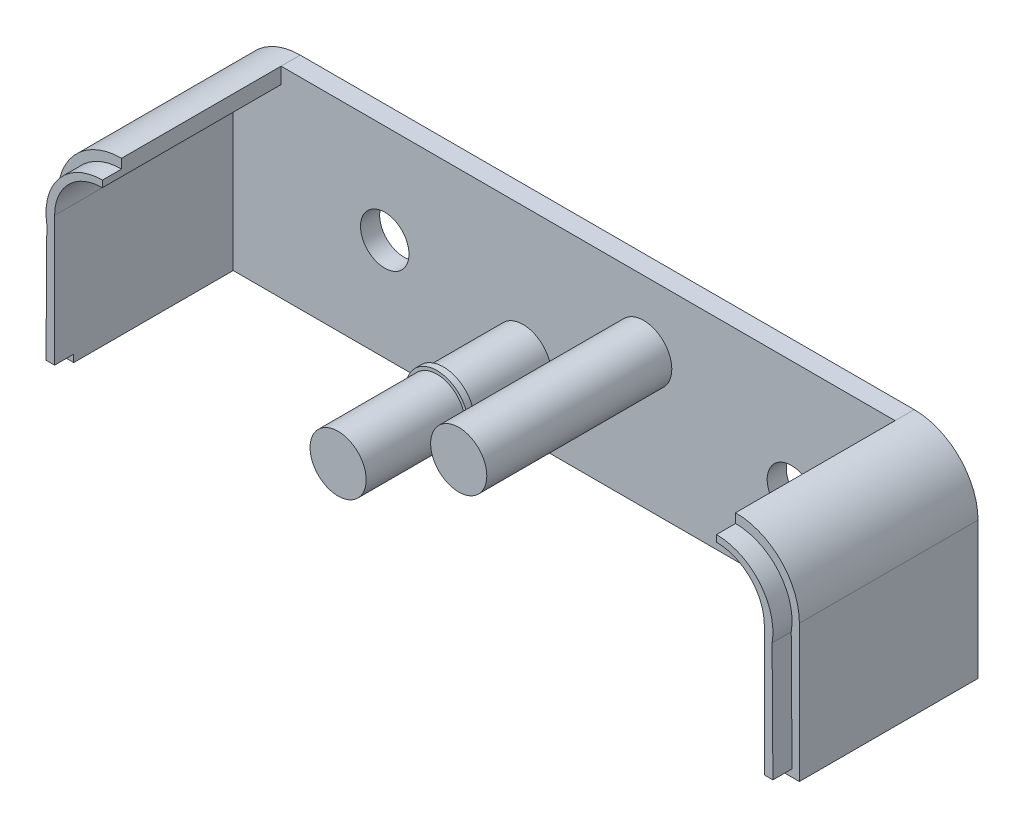
SolidWorks part; units mm, degrees
ref_plane "Front Plane" through (0, 0, 0) normal (0, 0, 1) x (1, 0, 0)
ref_plane "Top Plane" through (0, 0, 0) normal (0, 1, 0) x (1, 0, 0)
ref_plane "Right Plane" through (0, 0, 0) normal (1, 0, 0) x (0, 0, -1)
sketch "Sketch1" plane through (0, 0, 0) normal (0, 0, 1) x (1, 0, 0)
  line L0 (58.125, -2.25) -> (-58.125, -2.25) construction
  line L1 (-48.125, 15.75) -> (48.125, 15.75)
  line L2 (-58.125, 5.75) -> (-58.125, -15.75)
  line L3 (-58.125, -15.75) -> (58.125, -15.75)
  line L4 (58.125, 5.75) -> (58.125, -15.75)
  line L5 (-58.125, 15.75) -> (58.125, -15.75) construction
  line L6 (-58.125, -15.75) -> (58.125, 15.75) construction
  line L7 (31.875, 15.75) -> (31.875, -15.75) construction
  line L8 (-31.875, -15.75) -> (-31.875, 15.75) construction
  line L9 (-58.125, -0.25) -> (58.125, -0.25) construction
  arc A0 (48.125, 15.75) -> (58.125, 5.75) centre (48.125, 5.75) cw
  arc A1 (-48.125, 15.75) -> (-58.125, 5.75) centre (-48.125, 5.75) ccw
  circle A2 centre (31.875, -2.25) radius 3.8
  circle A3 centre (-31.875, 0.25) radius 3.8
  point P0 (0, 0)
  dimension "D3" = 10
  dimension "D6" = 7.6
  dimension "D8" = 7.6
  dimension "D1" = 116.25
  dimension "D2" = 31.5
  dimension "D4" = 13.5
  dimension "D5" = 26.25
  dimension "D7" = 15.5
  dimension "D9" = 26.25
extrude "Boss-Extrude2" add sketch "Sketch1" along normal blind 3
sketch "Sketch2" plane through (0, 0, 3) normal (0, 0, 1) x (1, 0, 0)
  line L0 (-18.625, 15.75) -> (-18.625, -15.75) construction
  line L1 (48.125, 15.75) -> (-48.125, 15.75) construction
  line L2 (-58.125, -15.75) -> (58.125, -15.75) construction
  line L3 (21.625, 15.75) -> (21.625, -15.75) construction
  line L4 (-58.125, 5.25) -> (58.125, 5.25) construction
  line L5 (-58.125, 5.75) -> (-58.125, -15.75) construction
  line L6 (58.125, -15.75) -> (58.125, 5.75) construction
  line L7 (8.725, 15.75) -> (8.725, -15.75) construction
  line L8 (-10.185, 15.75) -> (-10.185, -15.75) construction
  line L9 (-58.125, -4.75) -> (58.125, -4.75) construction
  line L10 (0.575, 5.25) -> (0.575, -15.75) construction
  line L11 (-18.335, -4.75) -> (-18.335, -15.75) construction
  line L26 (55.625, -15.75) -> (55.625, 5.75)
  line L27 (55.625, -15.75) -> (55.625, 5.75)
  line L28 (-55.625, -15.75) -> (-58.125, -15.75)
  line L29 (-55.625, 5.75) -> (-55.625, -15.75)
  line L30 (-55.625, 5.75) -> (-55.625, -15.75)
  line L31 (-58.125, -15.75) -> (-58.125, 5.25)
  line L32 (-48.125, 13.25) -> (-48.125, 15.75)
  line L33 (55.625, -15.75) -> (58.125, -15.75)
  line L34 (58.125, -15.75) -> (58.125, 5.25)
  line L35 (48.125, 13.25) -> (48.125, 15.75)
  circle A0 centre (-31.875, 0.25) radius 13.25 construction
  circle A1 centre (31.875, -2.25) radius 10.25 construction
  circle A2 centre (8.725, 5.25) radius 18 construction
  circle A3 centre (8.725, 5.25) radius 4.4
  circle A4 centre (8.725, 5.25) radius 8.15 construction
  circle A5 centre (-10.185, -4.75) radius 8.15 construction
  circle A6 centre (-10.185, -4.75) radius 4.4
  arc A10 (58.125, 5.75) -> (48.125, 15.75) centre (48.125, 5.75) ccw
  arc A11 (58.125, 5.75) -> (48.125, 15.75) centre (48.125, 5.75) ccw
  arc A13 (-48.125, 15.75) -> (-58.125, 5.75) centre (-48.125, 5.75) ccw
  arc A14 (-48.125, 15.75) -> (-58.125, 5.75) centre (-48.125, 5.75) ccw
  arc A28 (55.625, 5.75) -> (48.125, 13.25) centre (48.125, 5.75) ccw
  arc A29 (55.625, 5.75) -> (48.125, 13.25) centre (48.125, 5.75) ccw
  arc A32 (-48.125, 13.25) -> (-55.625, 5.75) centre (-48.125, 5.75) ccw
  arc A33 (-48.125, 13.25) -> (-55.625, 5.75) centre (-48.125, 5.75) ccw
  line M2 (58.125, -15.75) -> (58.125, 5.75)
  arc M3 (58.125, 5.75) -> (48.125, 15.75) centre (48.125, 5.75) ccw
  arc M5 (-48.125, 15.75) -> (-58.125, 5.75) centre (-48.125, 5.75) ccw
  line M6 (-58.125, 5.75) -> (-58.125, -15.75)
  line M7 (-58.125, -15.75) -> (58.125, -15.75)
  dimension "D1" = 26.5
  dimension "D2" = 20.5
  dimension "D6" = 8.8
  dimension "D8" = 10.76
  dimension "D9" = 8.8
  dimension "D10" = 19.2
  dimension "D7" = 31.5
  dimension "D11" = 11
  dimension "16" = 16.3
  dimension "D12" = 16.3
  dimension "D13" = 36
  dimension "D14" = 8.44
  dimension "D16" = 2.5
  dimension "D3" = 40.25
  dimension "D4" = 12.9
  dimension "D15" = 0.29
  dimension "D20" = 21
  dimension "D17" = 2.5
  dimension "D18" = 0
  dimension "D19" = 0
other "AlignGroup1"
other "AlignGroup2"
other "AlignGroup3"
other "AlignGroup4"
other "AlignGroup5"
extrude "Boss-Extrude3" add sketch "Sketch2" along normal blind 25 contours A3 | A6 | A29 L27 L35 M7 M2 M3 | A33 L32 L30 M5 M6 M7
sketch "Sketch5" plane through (0, 0, 28) normal (0, 0, 1) x (1, 0, 0)
  line L4 (-56.8469, 3.9347) -> (-56.975, -14.6)
  line L5 (0, 15.75) -> (0, -15.75) construction
  line L6 (48.125, 15.75) -> (-48.125, 15.75) construction
  line L7 (-55.625, -15.75) -> (55.625, -15.75) construction
  line L8 (-55.625, -14.6) -> (-56.975, -14.6)
  line L9 (-58.125, -15.75) -> (-55.625, -15.75) construction
  line L16 (55.625, -14.6) -> (55.625, 5.75)
  line L17 (48.125, 13.25) -> (48.125, 14.2852)
  line L18 (55.625, -14.6) -> (56.975, -14.6)
  line L19 (56.8469, 3.9347) -> (56.975, -14.6)
  line L28 (-48.125, 13.25) -> (-48.125, 15.75)
  line L29 (-58.125, 5.75) -> (-58.125, -15.75)
  line L30 (-58.125, -15.75) -> (-55.625, -15.75)
  line L31 (-55.625, -15.75) -> (-55.625, 5.75)
  line L32 (-48.125, 13.25) -> (-48.125, 14.2852)
  line L35 (-55.625, -14.6) -> (-55.625, 5.75)
  arc A2 (-48.125, 14.2852) -> (-56.8469, 3.9347) centre (-48.125, 5.4352) ccw
  arc A3 (48.125, 13.25) -> (55.625, 5.75) centre (48.125, 5.75) cw
  arc A4 (48.125, 14.2852) -> (56.8469, 3.9347) centre (48.125, 5.4352) cw
  arc A14 (-48.125, 13.25) -> (-55.625, 5.75) centre (-48.125, 5.75) ccw
  arc A15 (-48.125, 15.75) -> (-58.125, 5.75) centre (-48.125, 5.75) ccw
  arc A16 (-48.125, 13.25) -> (-55.625, 5.75) centre (-48.125, 5.75) ccw
  dimension "D1" = 1.35
  dimension "D3" = 0.3148
  dimension "D4" = 8.85
  dimension "D2" = 1.15
  dimension "D6" = 18.5352
  dimension "D5" = 0
sketch "Sketch10" plane through (0, 0, 28) normal (0, 0, 1) x (1, 0, 0)
  circle A1 centre (8.725, 5.25) radius 4.4
  circle A2 centre (8.725, 5.25) radius 4.4
  circle A3 centre (-10.185, -4.75) radius 4.4
  circle A4 centre (-10.185, -4.75) radius 4.4
  dimension "D1" = 0
  dimension "D2" = 0
extrude "Cut-Extrude3" cut sketch "Sketch10" against normal blind 1
extrude "Boss-Extrude5" add sketch "Sketch5" along normal blind 3
sketch "Sketch12" plane through (0, 0, 27) normal (0, 0, 1) x (1, 0, 0)
  circle A0 centre (-10.185, -4.75) radius 4.4 construction
  circle A1 centre (8.725, 5.25) radius 4.4 construction
  circle A2 centre (-10.185, -4.75) radius 4.4
  circle A3 centre (8.725, 5.25) radius 4.4
extrude "Boss-Extrude6" add sketch "Sketch12" along normal blind 5
ref_plane "Plane2" through (0, 0, 15.5) normal (0, 0, 1) x (1, 0, 0)
sketch "Sketch14" plane through (0, 0, 15.5) normal (0, 0, 1) x (1, 0, 0)
  circle A2 centre (-10.185, -4.75) radius 4.9
  circle A3 centre (-10.185, -4.75) radius 4.9
  dimension "D1" = 0.5
extrude "Boss-Extrude7" add sketch "Sketch14" along normal blind 1
